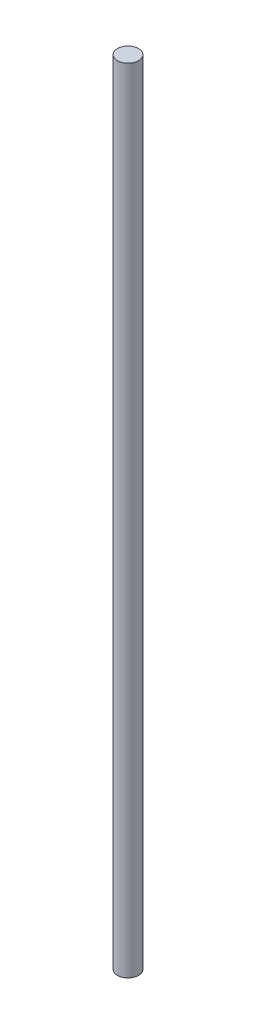
SolidWorks part; units mm, degrees
ref_plane "Front" through (0, 0, 0) normal (0, 0, 1) x (1, 0, 0)
ref_plane "Top" through (0, 0, 0) normal (0, 1, 0) x (1, 0, 0)
ref_plane "Right" through (0, 0, 0) normal (1, 0, 0) x (0, 0, -1)
sketch "Эскиз1" plane through (0, 0, 0) normal (0, 1, 0) x (1, 0, 0)
  circle A0 centre (0, 0) radius 6
extrude "Бобышка-Вытянуть1" add sketch "Эскиз1" along normal blind 450
